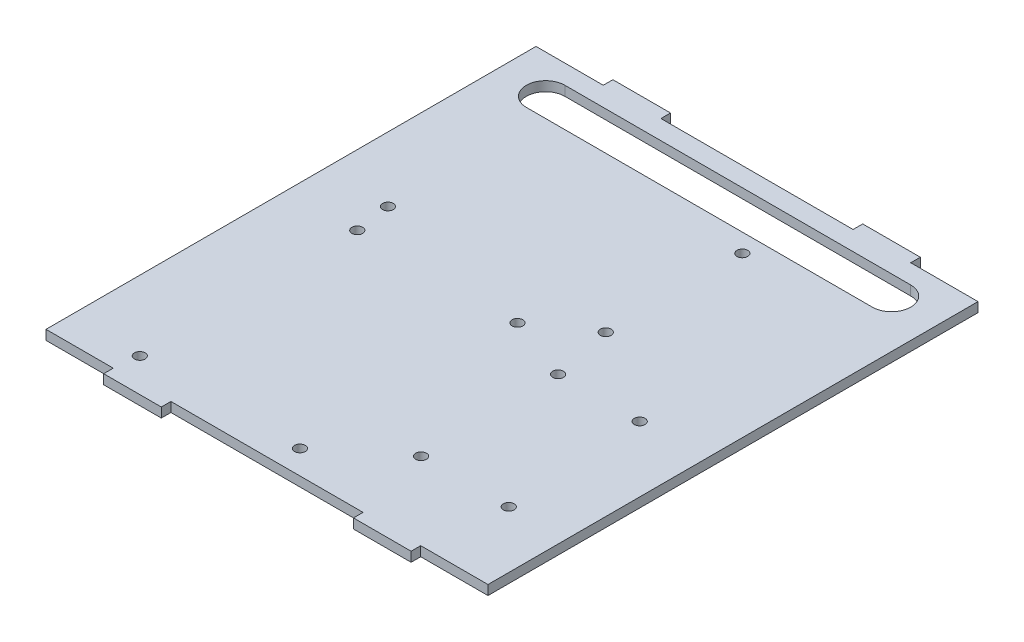
SolidWorks part; units mm, degrees
ref_plane "Front Plane" through (0, 0, 0) normal (0, 0, 1) x (1, 0, 0)
ref_plane "Top Plane" through (0, 0, 0) normal (0, 1, 0) x (1, 0, 0)
ref_plane "Right Plane" through (0, 0, 0) normal (1, 0, 0) x (0, 0, -1)
sketch "Sketch1" plane through (0, 0, 0) normal (0, 1, 0) x (1, 0, 0)
  line L1 (73.025, -80.9625) -> (-73.025, -80.9625)
  line L2 (73.025, -80.9625) -> (73.025, 80.9625)
  line L3 (73.025, 80.9625) -> (-73.025, 80.9625)
  line L4 (-73.025, -80.9625) -> (-73.025, 80.9625)
  line L5 (73.025, -80.9625) -> (-73.025, 80.9625) construction
  line L6 (73.025, 80.9625) -> (-73.025, -80.9625) construction
  point P0 (0, 0)
  dimension "D1" = 161.925
  dimension "D2" = 146.05
extrude "Boss-Extrude1" add sketch "Sketch1" along normal blind 3.175
sketch "Sketch2" plane through (0, 3.175, 0) normal (0, 1, 0) x (1, 0, 0)
  line L0 (73.025, 80.9625) -> (-73.025, 80.9625) construction
  line L1 (-50.8, 84.1375) -> (-31.75, 84.1375)
  line L2 (-50.8, 84.1375) -> (-50.8, 80.9625)
  line L3 (-50.8, 80.9625) -> (-31.75, 80.9625)
  line L4 (-31.75, 84.1375) -> (-31.75, 80.9625)
  line L5 (0, 0) -> (0, 50000) construction
  line L6 (31.75, 84.1375) -> (50.8, 84.1375)
  line L7 (31.75, 84.1375) -> (31.75, 80.9625)
  line L8 (31.75, 80.9625) -> (50.8, 80.9625)
  line L9 (50.8, 84.1375) -> (50.8, 80.9625)
  line L10 (0, 0) -> (-50000, 0) construction
  line L11 (50.8, -84.1375) -> (50.8, -80.9625)
  line L12 (31.75, -80.9625) -> (50.8, -80.9625)
  line L13 (31.75, -84.1375) -> (31.75, -80.9625)
  line L14 (31.75, -84.1375) -> (50.8, -84.1375)
  line L15 (-31.75, -84.1375) -> (-31.75, -80.9625)
  line L16 (-50.8, -80.9625) -> (-31.75, -80.9625)
  line L17 (-50.8, -84.1375) -> (-50.8, -80.9625)
  line L18 (-50.8, -84.1375) -> (-31.75, -84.1375)
  dimension "D1" = 19.05
  dimension "D2" = 3.175
  dimension "D3" = 63.5
extrude "Boss-Extrude2" add sketch "Sketch2" against normal up to surface (3.175 mm away) up to face at (0, 0, 0)
sketch "Sketch3" plane through (0, 3.175, 0) normal (0, 1, 0) x (1, 0, 0)
  line L0 (-57.15, 68.2625) -> (57.15, 68.2625) construction
  line L1 (-57.15, 74.6125) -> (57.15, 74.6125)
  line L2 (-57.15, 61.9125) -> (57.15, 61.9125)
  line L3 (31.75, 80.9625) -> (-31.75, 80.9625) construction
  arc A0 (-57.15, 74.6125) -> (-57.15, 61.9125) centre (-57.15, 68.2625) ccw
  arc A1 (57.15, 61.9125) -> (57.15, 74.6125) centre (57.15, 68.2625) ccw
  point P2 (0, 68.2625)
  dimension "D2" = 6.35
  dimension "D1" = 12.7
  dimension "D3" = 114.3
extrude "Cut-Extrude1" cut sketch "Sketch3" against normal through all
sketch "Sketch4" plane through (0, 3.175, 0) normal (0, 1, 0) x (1, 0, 0)
  circle A0 centre (54.229, -55.3085) radius 1.778
  circle A1 centre (25.273, -55.3085) radius 1.778
  circle A2 centre (24.4602, -9.2329) radius 1.778
  circle A3 centre (51.435, -9.2329) radius 1.778
  circle A4 centre (3.0226, -73.0885) radius 1.778
  circle A5 centre (-49.911, -73.0885) radius 1.778
  circle A6 centre (-49.911, -1.2065) radius 1.778
  circle A7 centre (3.0226, -1.2065) radius 1.778
  circle A8 centre (-51.689, 10.6807) radius 1.778
  circle A9 centre (20.2946, 10.6807) radius 1.778
  circle A10 centre (20.2946, 55.8165) radius 1.778
  dimension "D1" = 3.556
  dimension "D2" = 3.556
  dimension "D3" = 3.556
  dimension "D4" = 3.556
  dimension "D5" = 3.556
  dimension "D6" = 3.556
  dimension "D7" = 3.556
  dimension "D8" = 3.556
  dimension "D9" = 3.556
  dimension "D10" = 3.556
  dimension "D11" = 3.556
extrude "Cut-Extrude2" cut sketch "Sketch4" against normal up to next
